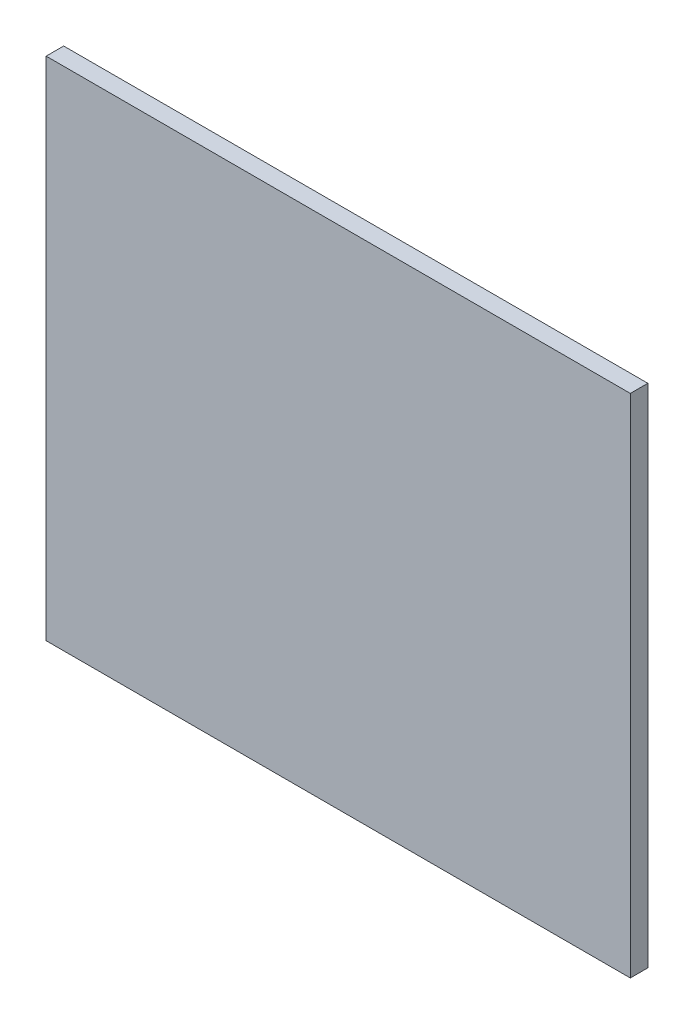
SolidWorks part; units mm, degrees
material "Perspex (TM) GS Acrylic Cast Sheet"
ref_plane "Front Plane" through (0, 0, 0) normal (0, 0, 1) x (1, 0, 0)
ref_plane "Top Plane" through (0, 0, 0) normal (0, 1, 0) x (1, 0, 0)
ref_plane "Right Plane" through (0, 0, 0) normal (1, 0, 0) x (0, 0, -1)
sketch "Sketch1" plane through (0, 0, 0) normal (0, 0, 1) x (1, 0, 0)
  line L1 (-75, -65) -> (75, -65)
  line L2 (-75, -65) -> (-75, 65)
  line L3 (-75, 65) -> (75, 65)
  line L4 (75, -65) -> (75, 65)
  line L5 (-75, -65) -> (75, 65) construction
  line L6 (-75, 65) -> (75, -65) construction
  point P0 (0, 0)
  dimension "D1" = 150
  dimension "D2" = 130
extrude "Boss-Extrude1" add sketch "Sketch1" along normal blind 4.5
sketch "Sketch2" plane through (0, 0, 4.5) normal (0, 0, 1) x (1, 0, 0)
  line L0 (0, 0) -> (0, 50000) construction
  line L1 (0, 0) -> (50000, 0) construction
  circle A0 centre (50, -30) radius 3.125
  circle A1 centre (-50, -30) radius 3.125
  circle A2 centre (-50, 30) radius 3.125
  circle A3 centre (50, 30) radius 3.125
  dimension "D1" = 6.25
  dimension "D2" = 30
  dimension "D3" = 50
